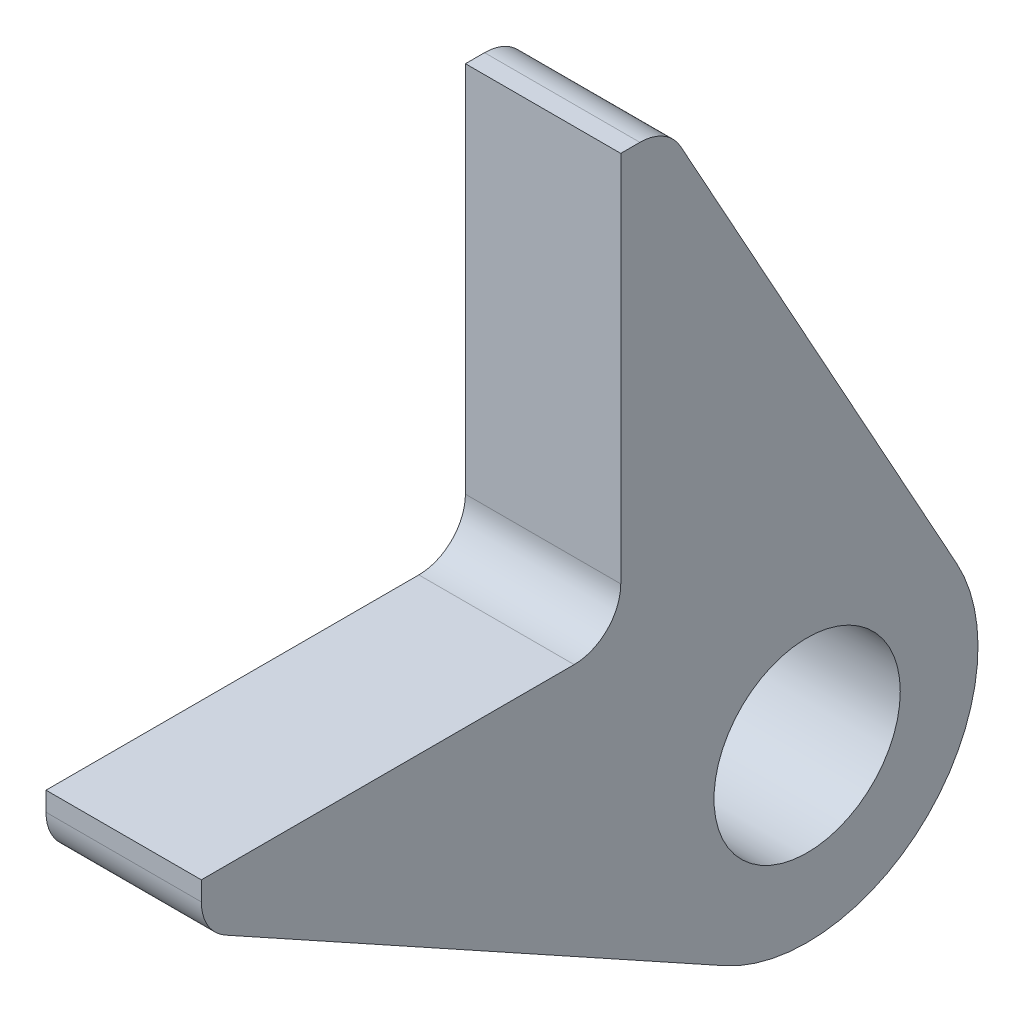
SolidWorks part; units mm, degrees
ref_plane "front" through (0, 0, 0) normal (0, 0, 1) x (1, 0, 0)
ref_plane "top" through (0, 0, 0) normal (0, 1, 0) x (1, 0, 0)
ref_plane "right" through (0, 0, 0) normal (1, 0, 0) x (0, 0, -1)
sketch "Sketch1" plane through (0, 0, 0) normal (1, 0, 0) x (0, 0, -1)
  line L0 (-38.0904, 123.8154) -> (-38.0904, 47.6154)
  line L1 (-47.6154, 38.0904) -> (-123.8154, 38.0904)
  line L2 (-123.8154, 38.0904) -> (-123.8154, 34.1823)
  line L3 (-118.9002, 25.8471) -> (-16.9025, -30.5624)
  line L4 (-38.0904, 123.8154) -> (-34.1823, 123.8154)
  line L5 (-25.8471, 118.9002) -> (30.5624, 16.9025)
  line L6 (0, 0) -> (73.66, 0) construction
  line L7 (0, 0) -> (-38.0904, 38.0904) construction
  circle A0 centre (0, 0) radius 19.0373
  arc A1 (-16.9025, -30.5624) -> (30.5624, 16.9025) centre (0, 0) ccw
  arc A2 (-47.6154, 38.0904) -> (-38.0904, 47.6154) centre (-47.6154, 47.6154) ccw
  arc A3 (-118.9002, 25.8471) -> (-123.8154, 34.1823) centre (-114.2904, 34.1823) cw
  arc A4 (-25.8471, 118.9002) -> (-34.1823, 123.8154) centre (-34.1823, 114.2904) ccw
  point P16 (-123.8154, 28.5654)
  point P19 (-28.5654, 123.8154)
  dimension "D1" = 38.0746
  dimension "D2" = 34.925
  dimension "D7" = 9.525
  dimension "D6" = 9.525
  dimension "D3" = 135
  dimension "D4" = 85.725
  dimension "D5" = 9.525
  dimension "D8" = 85.725
  dimension "D9" = 9.525
  dimension "D10" = 122.174
  dimension "D11" = 38.0904
extrude "Base-Extrude" add sketch "Sketch1" along normal mid plane 31.75
